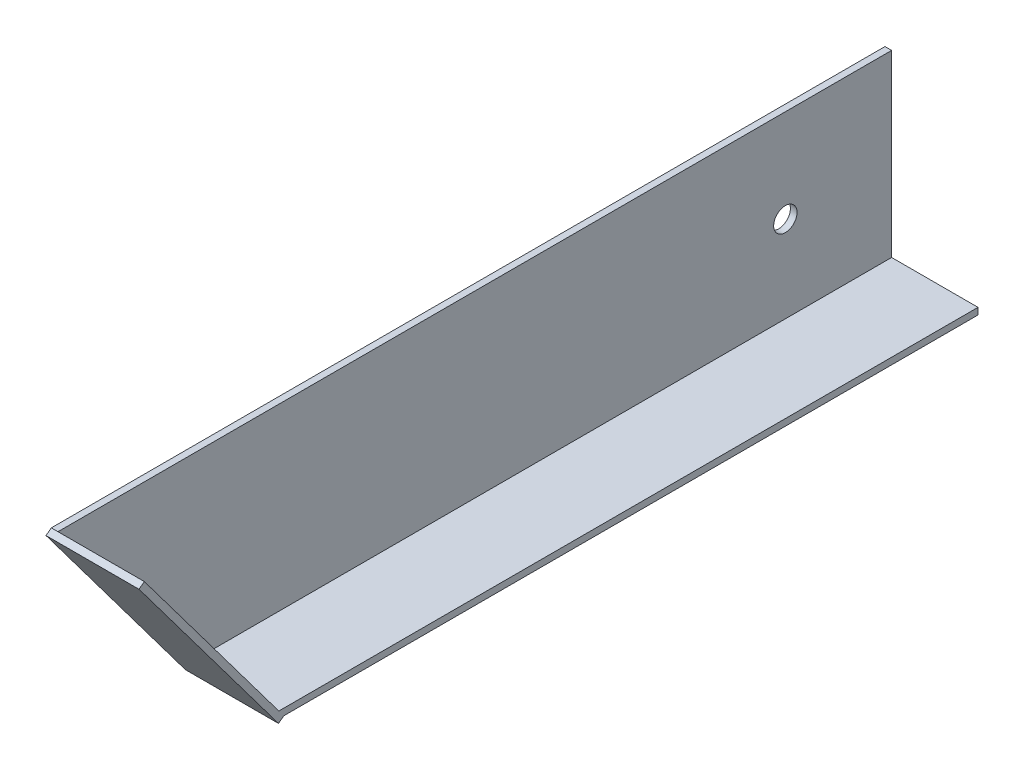
SolidWorks part; units mm, degrees
material "Galvanized Steel"
ref_plane "Front" through (0, 0, 0) normal (0, 0, 1) x (1, 0, 0)
ref_plane "Top" through (0, 0, 0) normal (0, 1, 0) x (1, 0, 0)
ref_plane "Right" through (0, 0, 0) normal (1, 0, 0) x (0, 0, -1)
sketch "Sketch1" plane through (0, 0, 0) normal (0, 0, 1) x (1, 0, 0)
  line L0 (3.175, 88.9) -> (3.175, 3.175)
  line L1 (0, 0) -> (44.45, 0)
  line L2 (0, 0) -> (0, 88.9)
  line L3 (0, 88.9) -> (3.175, 88.9)
  line L4 (44.45, 0) -> (44.45, 3.175)
  line L5 (3.175, 3.175) -> (44.45, 3.175)
  dimension "D1" = 44.45
  dimension "D2" = 3.175
  dimension "D3" = 88.9
extrude "Boss-Extrude1" add sketch "Sketch1" along normal mid plane 398.4625
sketch "Sketch4" plane through (3.175, 0, 0) normal (1, 0, 0) x (0, 0, -1)
  line L0 (199.2312, 3.175) -> (199.2312, 88.9) construction
  line L1 (199.2312, 88.9) -> (199.2312, 0) construction
  line L2 (-199.2312, 88.9) -> (-132.556, 0)
  line L3 (-199.2312, 0) -> (199.2312, 0) construction
  line L4 (-132.556, 0) -> (-199.2312, 0)
  line L5 (-199.2312, 0) -> (-199.2312, 88.9)
  circle A0 centre (148.4313, 44.45) radius 5.588
  point P6 (199.2312, 44.45)
  dimension "D2" = 11.176
  dimension "D1" = 50.8
  dimension "D3" = 53.13
extrude "Cut-Extrude3" cut sketch "Sketch4" along normal through all both and the other way through all
sketch "Sketch5" plane through (0, -63.6269, 84.8356) normal (0, -0.6, 0.8) x (1, 0, 0)
  line L1 (0, 79.5338) -> (44.45, 79.5338)
  line L2 (0, 79.5338) -> (0, 190.6589)
  line L3 (0, 190.6589) -> (44.45, 190.6589)
  line L4 (44.45, 79.5338) -> (44.45, 190.6589)
  point P5 (44.45, 70.485)
  point P7 (0, 181.6102)
extrude "Boss-Extrude3" add sketch "Sketch5" along normal blind 3.175
